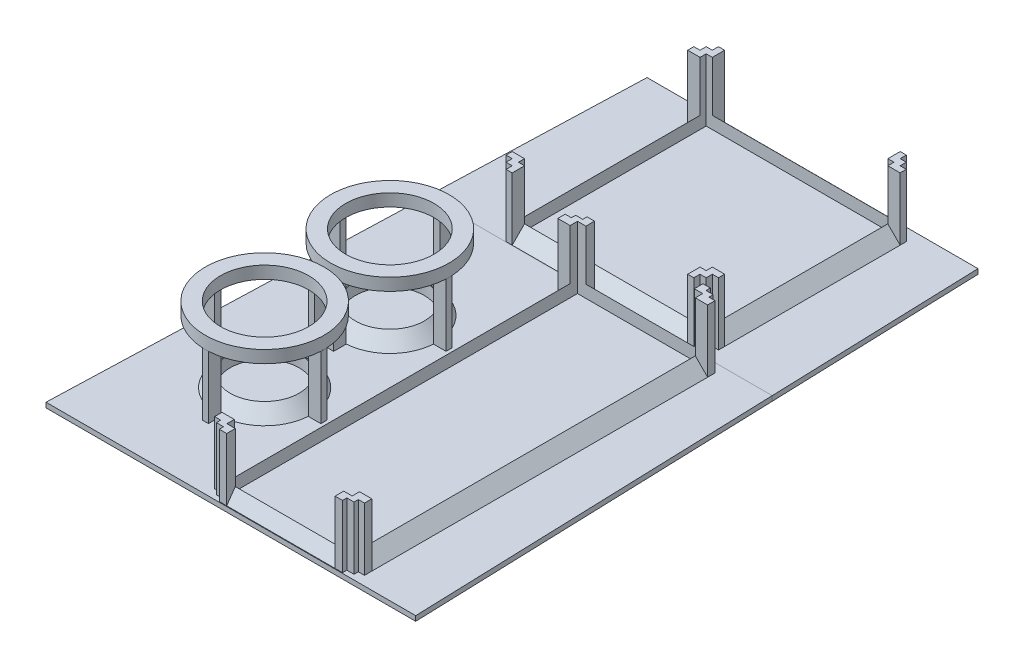
SolidWorks part; units mm, degrees
ref_plane "Front Plane" through (0, 0, 0) normal (0, 0, 1) x (1, 0, 0)
ref_plane "Top Plane" through (0, 0, 0) normal (0, 1, 0) x (1, 0, 0)
ref_plane "Right Plane" through (0, 0, 0) normal (1, 0, 0) x (0, 0, -1)
sketch "Sketch1" plane through (0, 0, 0) normal (0, 1, 0) x (1, 0, 0)
  line L0 (0, -118) -> (0, 118)
  line L1 (-67.135, 118) -> (67.135, 118)
  line L2 (-75, -118) -> (75, -118)
  line L3 (-67.135, 118) -> (-75, -118)
  line L4 (67.135, 118) -> (75, -118)
  point P4 (0, 0)
  point P8 (0, 118)
  point P11 (0, -118)
  dimension "D1" = 236
  dimension "D2" = 134.27
  dimension "D3" = 150
extrude "Boss-Extrude1" add sketch "Sketch1" along normal blind 2 contours L4 L1 L0 L2 | L1 L3 L2 L0
sketch "Sketch6" plane through (0, 2, 0) normal (0, 1, 0) x (1, 0, 0)
  line L0 (0, 74.85) -> (38.1, 74.85) construction
  line L1 (-38.1, 36.75) -> (38.1, 36.75)
  line L2 (-38.1, 36.75) -> (-38.1, 112.95)
  line L3 (-38.1, 112.95) -> (38.1, 112.95)
  line L4 (38.1, 36.75) -> (38.1, 112.95)
  line L5 (-38.1, 36.75) -> (38.1, 112.95) construction
  line L6 (-38.1, 112.95) -> (38.1, 36.75) construction
  line L7 (38.1, 74.85) -> (0, 74.85) construction
  line L8 (0, 74.85) -> (-38.1, 74.85) construction
  line L9 (-38.1, 74.85) -> (0, 74.85) construction
  line L10 (0, 74.85) -> (0, 112.95) construction
  line L11 (0, 112.95) -> (0, 36.75) construction
  line L12 (-67.135, 118) -> (67.135, 118) construction
  point P0 (0, 74.85)
  dimension "D1" = 76.2
  dimension "D2" = 5.05
ref_plane "Plane1" through (0, 0, -36.75) normal (0, 0, 1) x (1, 0, 0)
sketch "Sketch7" plane through (0, 0, -36.75) normal (0, 0, 1) x (1, 0, 0)
  line L0 (-38.1, 2) -> (-38.1, 7)
  line L1 (-38.1, 2) -> (38.1, 2) construction
  line L2 (-38.1, 7) -> (-43.1, 2)
  line L3 (-75, 2) -> (75, 2) construction
  line L4 (-43.1, 2) -> (-38.1, 2)
  dimension "D1" = 5
extrude "Boss-Extrude2" add sketch "Sketch7" against normal blind 76.2
mirror "Mirror1" about plane through (0, 0, 0) normal (1, 0, 0) of "Boss-Extrude2"
ref_plane "Plane2" through (0, 0, -74.85) normal (0, 0, 1) x (1, 0, 0)
ref_plane "Plane3" through (0, 0, 0) normal (1, 0, 0) x (0, 0, -1)
sketch "Sketch9" plane through (0, 0, 0) normal (1, 0, 0) x (0, 0, -1)
  line L0 (112.95, 2) -> (117.95, 2)
  line L1 (118, 2) -> (-118, 2) construction
  line L2 (112.95, 7) -> (112.95, 2) construction
  line L3 (112.95, 7) -> (112.95, 2)
  line L4 (112.95, 7) -> (117.95, 2)
extrude "Boss-Extrude7" add sketch "Sketch9" along normal mid plane 76
mirror "Mirror2" about plane through (0, 0, -74.85) normal (0, 0, 1) of "Boss-Extrude7"
sketch "Sketch11" plane through (0, 2, 0) normal (0, 1, 0) x (1, 0, 0)
  line L0 (-5.3455, -43.13) -> (-5.3455, 27.99)
  line L1 (-5.3455, 27.99) -> (45.4545, 27.99)
  line L2 (-5.3455, 27.99) -> (-5.3455, -114.25)
  line L3 (-5.3455, -114.25) -> (45.4545, -114.25)
  line L4 (45.4545, 27.99) -> (45.4545, -114.25)
  line L5 (-5.3455, 27.99) -> (20.0545, 27.99)
  line L7 (38, 31.75) -> (-38, 31.75) construction
  line L9 (-5.3455, -43.13) -> (45.4545, -43.13) construction
  line L10 (45.4545, -43.13) -> (20.0545, -43.13) construction
  line L11 (20.0545, -43.13) -> (20.0545, -26.8323) construction
  dimension "D1" = 142.24
  dimension "D2" = 50.8
  dimension "D4" = 3.76
ref_plane "Plane4" through (0, 0, 43.13) normal (0, 0, 1) x (1, 0, 0)
sketch "Sketch12" plane through (0, 0, 43.13) normal (0, 0, 1) x (1, 0, 0)
  line L0 (-10.3455, 2) -> (-5.3455, 2)
  line L1 (-38.1, 2) -> (38.1, 2) construction
  line L2 (-5.3455, 2) -> (45.4545, 2) construction
  line L3 (-5.3455, 2) -> (-5.3455, 7)
  line L4 (-5.3455, 7) -> (-10.3455, 2)
  dimension "D1" = 5
extrude "Boss-Extrude9" add sketch "Sketch12" along normal up to vertex (71.12 mm away) and the other way up to vertex (71.12 mm away) up to point (-5.3455, 2, 114.25) other way up to point (-5.3455, 2, -27.99)
ref_plane "Plane5" through (20.0545, 0, 0) normal (1, 0, 0) x (0, 0, -1)
mirror "Mirror4" about plane through (20.0545, 0, 0) normal (1, 0, 0) of "Boss-Extrude9"
sketch "Sketch15" plane through (0, 2, 0) normal (0, 1, 0) x (1, 0, 0)
  line L0 (-35.7576, -17.73) -> (-49.7276, -17.73) construction
  circle A0 centre (-35.7576, -17.73) radius 13.97
  dimension "D1" = 27.94
  dimension "D3" = 25.4
ref_plane "Plane6" through (0, 0, 17.73) normal (0, 0, 1) x (1, 0, 0)
sketch "Sketch17" plane through (0, 0, 17.73) normal (0, 0, 1) x (1, 0, 0)
  line L0 (-35.7576, 2) -> (-49.7276, 2) construction
  line L1 (-35.7576, 2) -> (-49.7276, 2) construction
  line L2 (-49.7276, 2) -> (-49.7276, 7)
  line L3 (-49.7276, 7) -> (-54.7276, 2)
  line L4 (-54.7276, 2) -> (-49.7276, 2)
  line L5 (-35.7576, 2) -> (-35.7576, 11.5229) construction
  dimension "D1" = 90
  dimension "D2" = 5
  dimension "D3" = 13.97
revolve "Revolve1" add sketch "Sketch17" angle 360 about L5
ref_plane "Plane8" through (0, 0, 43.13) normal (0, 0, 1) x (1, 0, 0)
mirror "Mirror7" about plane through (0, 0, 43.13) normal (0, 0, 1) of "Revolve1"
sketch "Sketch19" plane through (0, 2, 0) normal (0, 1, 0) x (1, 0, 0)
  line L0 (-59.8076, -16.48) -> (-59.8076, -18.98)
  line L1 (-37.0076, -41.78) -> (-34.5076, -41.78)
  line L2 (-37.0076, -41.78) -> (-37.0076, -36.78)
  line L3 (-37.0076, -36.78) -> (-34.5076, -36.78)
  line L4 (-34.5076, -41.78) -> (-34.5076, -36.78)
  line L5 (-37.0076, -41.78) -> (-34.5076, -36.78) construction
  line L6 (-37.0076, -36.78) -> (-34.5076, -41.78) construction
  line L7 (-59.8076, -18.98) -> (-54.8076, -18.98)
  line L8 (-59.8076, -16.48) -> (-54.8076, -16.48)
  line L9 (-54.8076, -16.48) -> (-54.8076, -18.98)
  line L10 (-59.8076, -16.48) -> (-54.8076, -18.98) construction
  line L11 (-54.8076, -16.48) -> (-59.8076, -18.98) construction
  line L12 (-34.5076, 6.32) -> (-37.0076, 6.32)
  line L13 (-37.0076, 6.32) -> (-37.0076, 1.32)
  line L14 (-34.5076, 6.32) -> (-34.5076, 1.32)
  line L15 (-34.5076, 1.32) -> (-37.0076, 1.32)
  line L16 (-34.5076, 6.32) -> (-37.0076, 1.32) construction
  line L17 (-34.5076, 1.32) -> (-37.0076, 6.32) construction
  line L18 (-11.7076, -18.98) -> (-11.7076, -16.48)
  line L19 (-11.7076, -16.48) -> (-16.7076, -16.48)
  line L20 (-11.7076, -18.98) -> (-16.7076, -18.98)
  line L21 (-16.7076, -18.98) -> (-16.7076, -16.48)
  line L22 (-11.7076, -18.98) -> (-16.7076, -16.48) construction
  line L23 (-16.7076, -18.98) -> (-11.7076, -16.48) construction
  circle A0 centre (-35.7576, -17.73) radius 19.05
  point P3 (-35.7576, -39.28)
  point P11 (-57.3076, -17.73)
  point P16 (-35.7576, 3.82)
  point P21 (-14.2076, -17.73)
  point P26 (-35.7576, -17.73)
  dimension "D1" = 38.1
  dimension "D2" = 2.5
  dimension "D3" = 5
  dimension "D4" = 19.05
  dimension "D5" = 4
extrude "Boss-Extrude13" add sketch "Sketch19" along normal blind 25.4 contours L14 L15 L13 L12 | L19 L21 L20 L18 | L4 L3 L2 L1 | L7 L9 L8 L0
sketch "Sketch20" plane through (0, 27.4, 0) normal (0, 1, 0) x (1, 0, 0)
  circle A0 centre (-35.7576, -17.73) radius 17.907
  circle A1 centre (-35.7576, -17.73) radius 24.05
  dimension "D1" = 35.814
extrude "Boss-Extrude14" add sketch "Sketch20" along normal blind 5
mirror "Mirror8" about plane through (0, 0, 43.13) normal (0, 0, 1) of "Boss-Extrude13", "Boss-Extrude14"
sketch "Sketch21" plane through (0, 2, 0) normal (0, 1, 0) x (1, 0, 0)
  line L0 (-43.1, 112.95) -> (-43.1, 36.75) construction
  line L1 (-38.1, 112.95) -> (-43.1, 112.95)
  line L2 (-38.1, 112.95) -> (-38.1, 110.45)
  line L3 (-38.1, 110.45) -> (-43.1, 110.45)
  line L4 (-43.1, 112.95) -> (-43.1, 110.45)
  line L5 (38, 117.95) -> (-38, 117.95) construction
  line L6 (-38.1, 112.95) -> (-35.6, 112.95)
  line L7 (-38.1, 112.95) -> (-38.1, 117.95)
  line L8 (-38.1, 117.95) -> (-35.6, 117.95)
  line L9 (-35.6, 112.95) -> (-35.6, 117.95)
  line L10 (43.1, 112.95) -> (43.1, 36.75) construction
  line L11 (38.1, 112.95) -> (43.1, 112.95)
  line L12 (38.1, 112.95) -> (38.1, 110.45)
  line L13 (38.1, 110.45) -> (43.1, 110.45)
  line L14 (43.1, 112.95) -> (43.1, 110.45)
  line L15 (38, 31.75) -> (-38, 31.75) construction
  line L16 (38.1, 112.95) -> (35.6, 112.95)
  line L17 (38.1, 112.95) -> (38.1, 117.95)
  line L18 (38.1, 117.95) -> (35.6, 117.95)
  line L19 (35.6, 112.95) -> (35.6, 117.95)
  line L20 (38.1, 36.75) -> (43.1, 36.75)
  line L21 (38.1, 36.75) -> (38.1, 39.25)
  line L22 (38.1, 39.25) -> (43.1, 39.25)
  line L23 (43.1, 36.75) -> (43.1, 39.25)
  line L24 (38.1, 36.75) -> (35.6, 36.75)
  line L25 (38.1, 36.75) -> (38.1, 31.75)
  line L26 (38.1, 31.75) -> (35.6, 31.75)
  line L27 (35.6, 36.75) -> (35.6, 31.75)
  line L29 (-38.1, 36.75) -> (-43.1, 36.75)
  line L30 (-38.1, 36.75) -> (-38.1, 39.25)
  line L31 (-38.1, 39.25) -> (-43.1, 39.25)
  line L32 (-43.1, 36.75) -> (-43.1, 39.25)
  line L33 (-38.1, 36.75) -> (-35.6, 36.75)
  line L34 (-38.1, 36.75) -> (-38.1, 31.75)
  line L35 (-38.1, 31.75) -> (-35.6, 31.75)
  line L36 (-35.6, 36.75) -> (-35.6, 31.75)
  line L37 (-38.1, 112.95) -> (-40.6, 112.95)
  line L38 (-38.1, 112.95) -> (-38.1, 115.45)
  line L39 (-38.1, 115.45) -> (-40.6, 115.45)
  line L40 (-40.6, 112.95) -> (-40.6, 115.45)
  line L41 (38.1, 112.95) -> (40.6, 112.95)
  line L42 (38.1, 112.95) -> (38.1, 115.45)
  line L43 (38.1, 115.45) -> (40.6, 115.45)
  line L44 (40.6, 112.95) -> (40.6, 115.45)
  line L45 (38.1, 36.75) -> (40.6, 36.75)
  line L46 (38.1, 36.75) -> (38.1, 34.25)
  line L47 (38.1, 34.25) -> (40.6, 34.25)
  line L48 (40.6, 36.75) -> (40.6, 34.25)
  line L49 (-38.1, 36.75) -> (-40.6, 36.75)
  line L50 (-38.1, 36.75) -> (-38.1, 34.25)
  line L51 (-38.1, 34.25) -> (-40.6, 34.25)
  line L52 (-40.6, 36.75) -> (-40.6, 34.25)
  dimension "D1" = 2.5
  dimension "D2" = 2.5
  dimension "D3" = 2.5
  dimension "D4" = 2.5
  dimension "D5" = 2.5
  dimension "D6" = 2.5
  dimension "D7" = 2.5
  dimension "D8" = 2.5
  dimension "D9" = 2.5
extrude "Boss-Extrude15" add sketch "Sketch21" along normal blind 25.4 contours L6 L9 L8 L7 | L40 L1 L7 L39 | L1 L4 L3 L2 | L32 L29 L30 L31 | L29 L52 L51 L34 | L36 L33 L34 L35 | L20 L23 L22 L21 | L48 L20 L25 L47 | L24 L27 L26 L25 | L19 L16 L17 L18 | L14 L11 L12 L13 | L11 L44 L43 L17
ref_plane "Plane10" through (20.0545, 0, 0) normal (1, 0, 0) x (0, 0, -1)
sketch "Sketch23" plane through (20.0545, 0, 0) normal (1, 0, 0) x (0, 0, -1)
  line L0 (27.99, 2) -> (27.99, 7)
  line L1 (27.99, 2) -> (-114.25, 2) construction
  line L2 (118, 2) -> (-118, 2) construction
  line L3 (-114.25, 7) -> (27.99, 7) construction
  line L4 (27.99, 7) -> (31.49, 2)
  line L5 (31.49, 2) -> (27.99, 2)
  dimension "D1" = 3.5
extrude "Boss-Extrude16" add sketch "Sketch23" along normal mid plane 50
mirror "Mirror10" about plane through (0, 0, 43.13) normal (0, 0, 1) of "Boss-Extrude16"
sketch "Sketch24" plane through (0, 2, 0) normal (0, 1, 0) x (1, 0, 0)
  line L0 (-4.9455, 31.49) -> (-1.9455, 31.49)
  line L1 (45.0545, 31.49) -> (-4.9455, 31.49) construction
  line L2 (-1.9455, 31.49) -> (-1.9455, 27.99)
  line L3 (-5.3455, 27.99) -> (45.4545, 27.99) construction
  line L4 (-1.9455, 27.99) -> (-4.9455, 27.99)
  line L5 (-4.9455, 27.99) -> (-4.9455, 31.49)
  line L6 (-5.3455, 27.99) -> (-10.3455, 27.99)
  line L7 (-10.3455, 27.99) -> (-10.3455, 24.99)
  line L8 (-10.3455, -114.25) -> (-10.3455, 27.99) construction
  line L9 (-10.3455, 24.99) -> (-5.3455, 24.99)
  line L10 (-5.3455, -43.13) -> (-5.3455, 27.99) construction
  line L11 (-5.3455, 24.99) -> (-5.3455, 27.99)
  line L12 (-7.8455, 27.99) -> (-7.8455, 29.74)
  line L13 (-7.8455, 29.74) -> (-4.9455, 29.74)
  line L14 (-17.82, -43.13) -> (17.82, -43.13) construction
  line L15 (-4.9455, -114.25) -> (-4.9455, -117.75)
  line L16 (-1.9455, -117.75) -> (-1.9455, -114.25)
  line L17 (-4.9455, -117.75) -> (-1.9455, -117.75)
  line L18 (-7.8455, -116) -> (-4.9455, -116)
  line L19 (-7.8455, -114.25) -> (-7.8455, -116)
  line L20 (-5.3455, -111.25) -> (-5.3455, -114.25)
  line L21 (-10.3455, -111.25) -> (-5.3455, -111.25)
  line L22 (-10.3455, -114.25) -> (-10.3455, -111.25)
  line L23 (-5.3455, -114.25) -> (-10.3455, -114.25)
  line L24 (-1.9455, -114.25) -> (-4.9455, -114.25)
  line L25 (20.0545, -14.85) -> (20.0545, 14.85) construction
  line L26 (42.0545, -114.25) -> (45.0545, -114.25)
  line L27 (45.4545, -114.25) -> (50.4545, -114.25)
  line L28 (50.4545, -114.25) -> (50.4545, -111.25)
  line L29 (50.4545, -111.25) -> (45.4545, -111.25)
  line L30 (45.4545, -111.25) -> (45.4545, -114.25)
  line L31 (47.9545, -114.25) -> (47.9545, -116)
  line L32 (47.9545, -116) -> (45.0545, -116)
  line L33 (45.0545, -117.75) -> (42.0545, -117.75)
  line L34 (42.0545, -117.75) -> (42.0545, -114.25)
  line L35 (45.0545, -114.25) -> (45.0545, -117.75)
  line L36 (45.0545, 27.99) -> (45.0545, 31.49)
  line L37 (42.0545, 31.49) -> (42.0545, 27.99)
  line L38 (45.0545, 31.49) -> (42.0545, 31.49)
  line L39 (47.9545, 29.74) -> (45.0545, 29.74)
  line L40 (47.9545, 27.99) -> (47.9545, 29.74)
  line L41 (45.4545, 24.99) -> (45.4545, 27.99)
  line L42 (50.4545, 24.99) -> (45.4545, 24.99)
  line L43 (50.4545, 27.99) -> (50.4545, 24.99)
  line L44 (45.4545, 27.99) -> (50.4545, 27.99)
  line L45 (42.0545, 27.99) -> (45.0545, 27.99)
  line L46 (45.4545, 27.99) -> (45.0545, 27.99)
  line L47 (-4.9455, 27.99) -> (-5.3455, 27.99)
  line L48 (-4.9455, -114.25) -> (-5.3455, -114.25)
  line L49 (45.0545, -114.25) -> (45.4545, -114.25)
  point P24 (-4.9455, 29.74)
  dimension "D1" = 3
extrude "Boss-Extrude17" add sketch "Sketch24" along normal up to surface (25.4 mm away) contours L9 L11 L6 L7 | L47 L5 L13 L12 L6 | L5 L4 L2 L0 | L37 L45 L36 L38 | L46 L44 L40 L39 L36 | L44 L41 L42 L43 | L29 L30 L27 L28 | L49 L35 L32 L31 L27 | L35 L26 L34 L33 | L16 L24 L15 L17 | L15 L48 L23 L19 L18 | L23 L20 L21 L22 up to face at (-39.1, 27.4, -35.75)
ref_plane "Plane11" through (0, 0, -31.62) normal (0, 0, -1) x (-1, 0, 0)
split "Split1" trim tools "Plane11" bodies to split 128 resulting bodies 129 130
delete or keep bodies "Body-Delete/Keep 3" [suppressed] type delete bodies bodies 130
delete or keep bodies "Body-Delete/Keep 4" [suppressed] type delete bodies bodies 129
